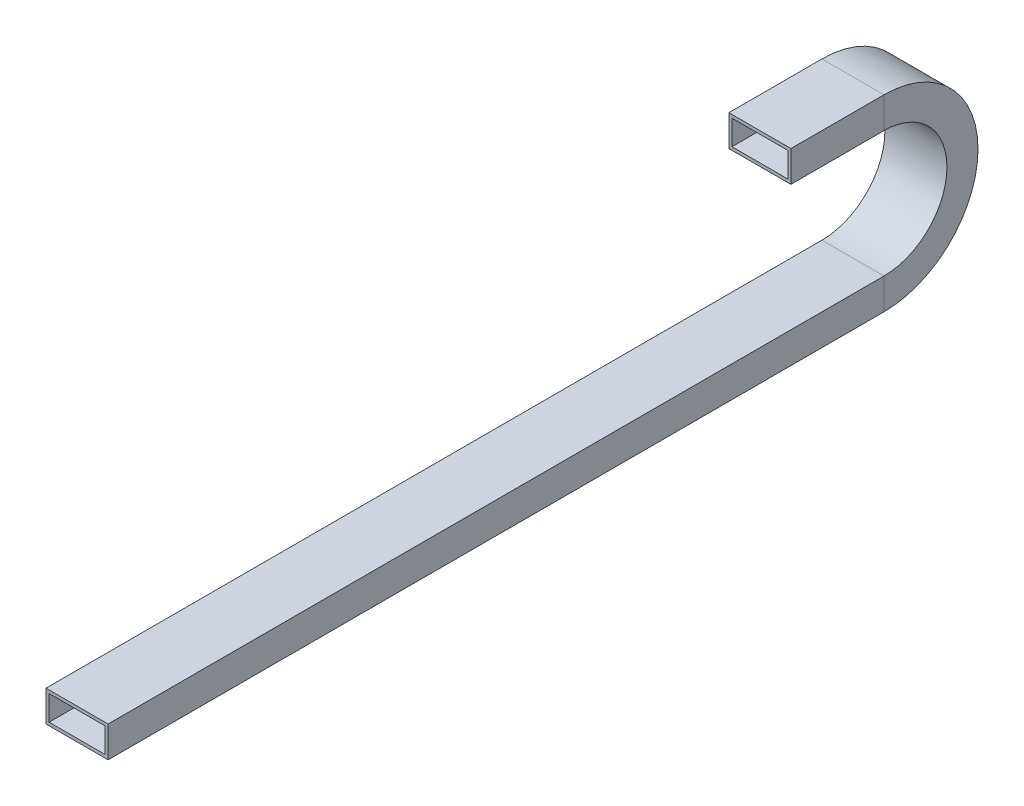
SolidWorks part; units mm, degrees
ref_plane "Front" through (0, 0, 0) normal (0, 0, 1) x (1, 0, 0)
ref_plane "Top" through (0, 0, 0) normal (0, 1, 0) x (1, 0, 0)
ref_plane "Right" through (0, 0, 0) normal (1, 0, 0) x (0, 0, -1)
sketch "Esquisse1" plane through (0, 0, 0) normal (0, 0, 1) x (1, 0, 0)
  line L1 (0, 0) -> (20, 0)
  line L2 (0, 0) -> (0, 10)
  line L3 (0, 10) -> (20, 10)
  line L4 (20, 0) -> (20, 10)
  line L5 (10, 1) -> (10, 0) construction
  line L6 (1, 9) -> (19, 9)
  line L7 (1, 9) -> (1, 1)
  line L8 (1, 1) -> (19, 1)
  line L9 (19, 9) -> (19, 1)
  line L10 (0, 5) -> (1, 5) construction
  dimension "D1" = 20
  dimension "D2" = 10
  dimension "D3" = 1
  dimension "D4" = 1
sketch "Esquisse2" plane through (0, 0, 0) normal (1, 0, 0) x (0, 0, -1)
  line L0 (0, 0) -> (0, 4.5691) construction
  line L1 (0, 0) -> (0, 10) construction
  line L2 (0, 0) -> (0, 10) construction
  line L3 (0, 2.2846) -> (250, 2.2846)
  line L4 (250, 2.2846) -> (250, 58.2846) construction
  line L5 (250, 58.2846) -> (220, 58.2846)
  arc A0 (250, 2.2846) -> (250, 58.2846) centre (250, 30.2846) ccw
  dimension "D1" = 28
  dimension "D2" = 250
  dimension "D3" = 30
sweep "Balayage1" add profiles "Esquisse1" path "Esquisse2"
